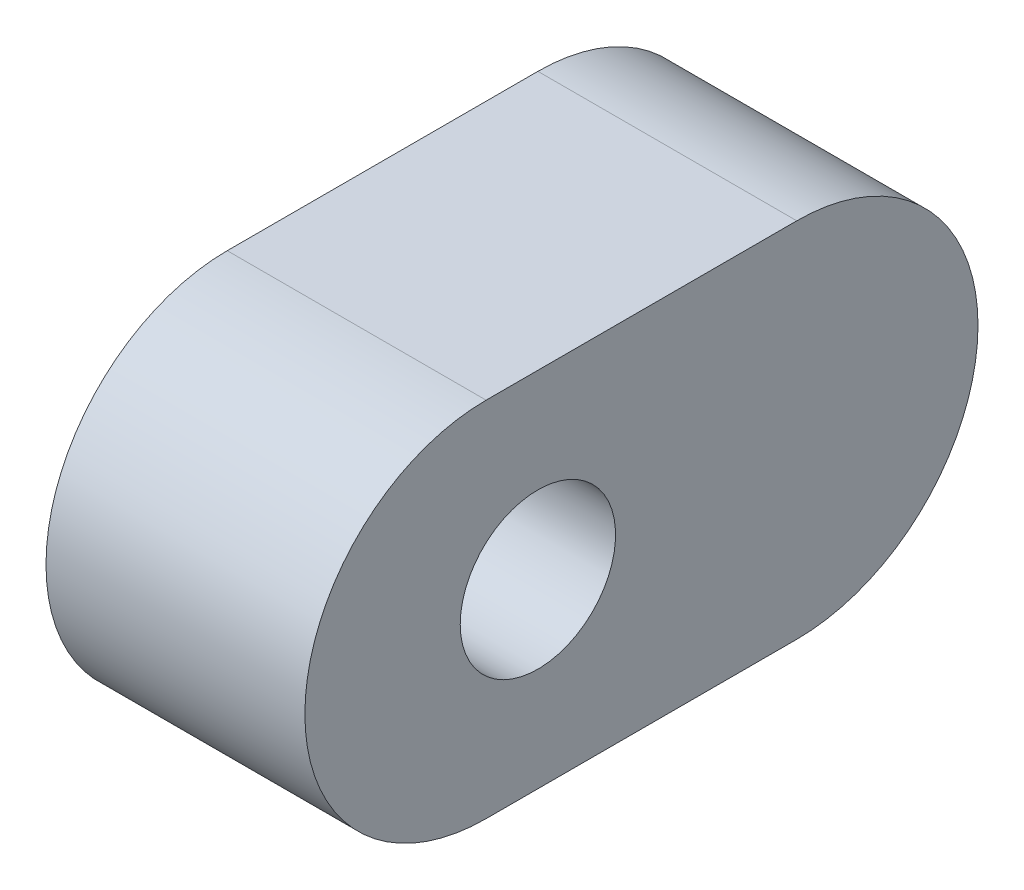
SolidWorks part; units mm, degrees
ref_plane "Front Plane" through (0, 0, 0) normal (1, 0, 0) x (0, 1, 0)
ref_plane "Top Plane" through (0, 0, 0) normal (0, 0, 1) x (0, 1, 0)
ref_plane "Right Plane" through (0, 0, 0) normal (0, 1, 0) x (-1, 0, 0)
sketch "Sketch1" plane through (0, 0, 0) normal (1, 0, 0) x (0, 1, 0)
  line L1 (-3.175, 0) -> (-3.175, -7.62)
  line L3 (3.175, 0) -> (3.175, -7.62)
  circle A0 centre (0, 0) radius 1.905
  arc A1 (3.175, 0) -> (-3.175, 0) centre (0, 0) ccw
  arc A2 (-3.175, -7.62) -> (3.175, -7.62) centre (0, -7.62) ccw
  point P3 (0, 3.175)
  point P5 (0, -10.795)
  dimension "D1" = 3.81
  dimension "D3" = 13.97
  dimension "D4" = 6.35
extrude "Boss-Extrude1" add sketch "Sketch1" along normal blind 6.35
sketch "Sketch2" plane through (6.35, 0, 0) normal (1, 0, 0) x (0, 1, 0)
  line L0 (-4.445, 0) -> (-4.445, -7.62)
  line L1 (4.445, -7.62) -> (4.445, 0)
  line L2 (-3.175, 0) -> (-3.175, -7.62)
  line L3 (3.175, -7.62) -> (3.175, 0)
  line L4 (-3.175, 0) -> (-3.175, -7.62)
  line L5 (3.175, -7.62) -> (3.175, 0)
  circle A0 centre (0, 0) radius 1.905 construction
  circle A1 centre (0, 0) radius 1.905
  arc A2 (3.175, 0) -> (-3.175, 0) centre (0, 0) ccw
  arc A3 (-3.175, -7.62) -> (3.175, -7.62) centre (0, -7.62) ccw
  arc A4 (3.175, 0) -> (-3.175, 0) centre (0, 0) ccw
  arc A5 (-3.175, -7.62) -> (3.175, -7.62) centre (0, -7.62) ccw
  arc A6 (-4.445, -7.62) -> (4.445, -7.62) centre (0, -7.62) ccw
  arc A7 (4.445, 0) -> (-4.445, 0) centre (0, 0) ccw
  arc M10 (3.175, 0) -> (-3.175, 0) centre (0, 0) ccw
  line M11 (-3.175, 0) -> (-3.175, -7.62)
  arc M12 (-3.175, -7.62) -> (3.175, -7.62) centre (0, -7.62) ccw
  line M13 (3.175, -7.62) -> (3.175, 0)
  dimension "D1" = 0
  dimension "D2" = 1.27
extrude "Boss-Extrude2" add sketch "Sketch2" against normal blind 6.35 contours L1 A7 L0 A6 M10 M13 M12 M11
sketch "Sketch6" plane through (6.35, 0, 0) normal (1, 0, 0) x (0, 1, 0)
  circle A0 centre (0, 0) radius 1.905
extrude "Boss-Extrude4" add sketch "Sketch6" against normal up to surface (6.35 mm away) up to face at (0, 0, -1.905)
sketch "Sketch7" plane through (0, 0, 0) normal (-1, 0, 0) x (0, -1, 0)
  circle A0 centre (0, -1.27) radius 1.905
  dimension "D2" = 3.81
  dimension "D1" = 1.27
extrude "Cut-Extrude3" cut sketch "Sketch7" against normal through all
sketch "Sketch8" plane through (0, 0, 0) normal (-1, 0, 0) x (0, -1, 0)
  circle A0 centre (0, -1.27) radius 3.048
  dimension "D1" = 6.096
extrude "Cut-Extrude4" cut sketch "Sketch8" against normal blind 2.54
